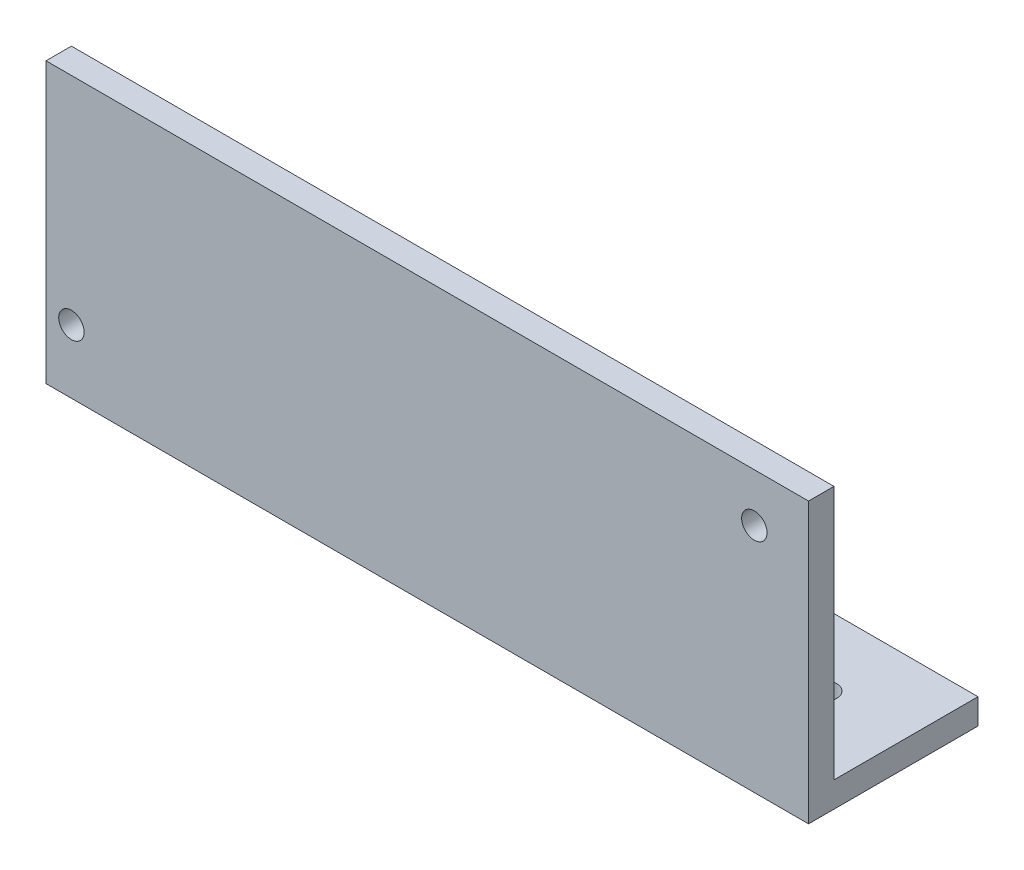
SolidWorks part; units mm, degrees
ref_plane "Front Plane" through (0, 0, 0) normal (0, 0, 1) x (1, 0, 0)
ref_plane "Top Plane" through (0, 0, 0) normal (0, 1, 0) x (1, 0, 0)
ref_plane "Right Plane" through (0, 0, 0) normal (1, 0, 0) x (0, 0, -1)
sketch "Sketch1" plane through (0, 0, 0) normal (0, 1, 0) x (1, 0, 0)
  line L0 (-13.8565, -4.4888) -> (76.1435, -4.4888) construction
  line L1 (-13.8565, -7.4888) -> (76.1435, -7.4888)
  line L2 (-13.8565, -7.4888) -> (-13.8565, 12.5112)
  line L3 (-13.8565, 12.5112) -> (76.1435, 12.5112)
  line L4 (76.1435, -7.4888) -> (76.1435, 12.5112)
  line L5 (-9.7129, 12.5112) -> (-9.7129, -4.4888) construction
  circle A0 centre (-6.3381, 4.0112) radius 1.5
  circle A1 centre (66.471, 4.0112) radius 1.5
  point P13 (-9.7129, 4.0112)
  dimension "D3" = 3
  dimension "D4" = 3
  dimension "D1" = 90
  dimension "D2" = 20
  dimension "D5" = 3
extrude "Boss-Extrude1" add sketch "Sketch1" along normal blind 3
sketch "Sketch2" plane through (0, 0, 7.4888) normal (0, 0, 1) x (1, 0, 0)
  line L0 (76.1435, 3) -> (76.1435, 0) construction
  line L1 (-13.8565, 3) -> (76.1435, 3)
  line L2 (-13.8565, 3) -> (-13.8565, 33)
  line L3 (-13.8565, 33) -> (76.1435, 33)
  line L4 (76.1435, 3) -> (76.1435, 33)
  circle A0 centre (-10.8565, 7.5) radius 1.5
  circle A1 centre (69.7435, 27.3) radius 1.5
  dimension "D2" = 3
  dimension "D3" = 3
  dimension "D1" = 30
  dimension "D4" = 4.5
  dimension "D5" = 3
  dimension "D6" = 80.6
  dimension "D7" = 19.8
extrude "Boss-Extrude2" add sketch "Sketch2" against normal blind 3
